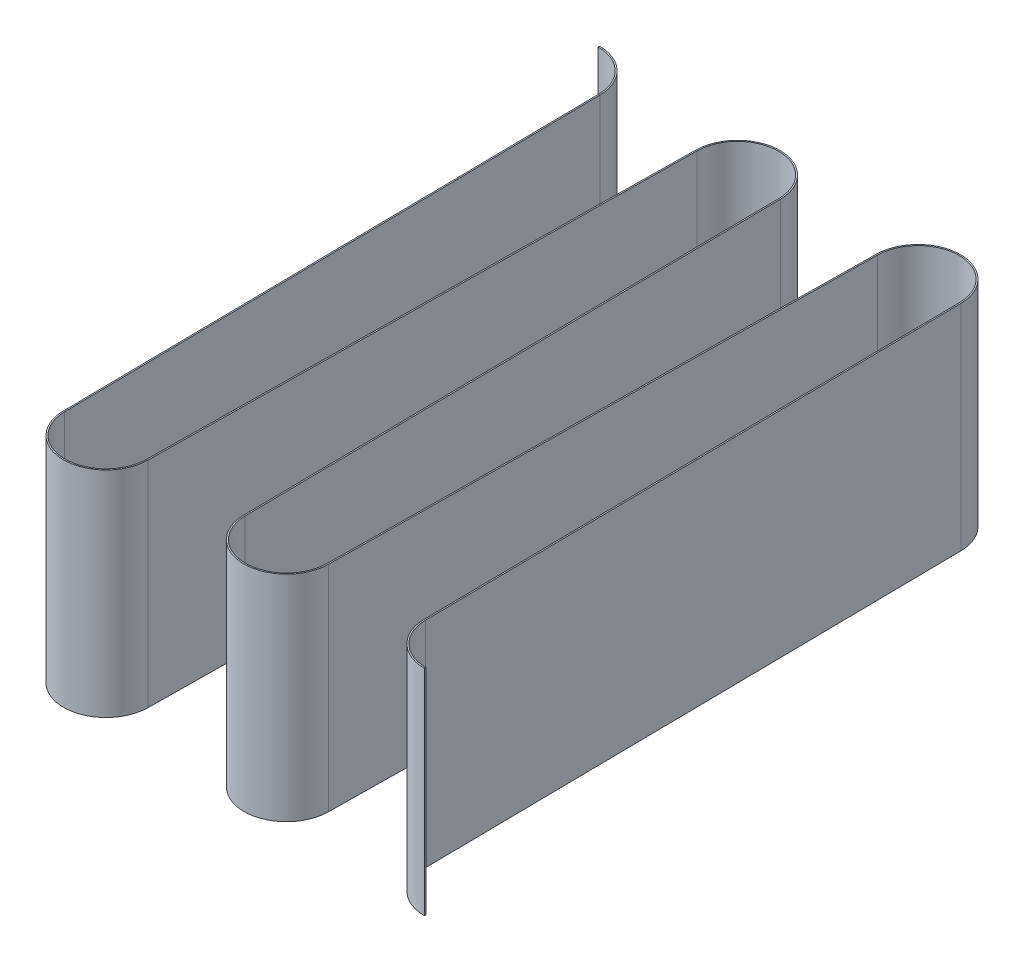
SolidWorks part; units mm, degrees
material "Corrugated Paper"
ref_plane "Front" through (0, 0, 0) normal (0, 0, 1) x (1, 0, 0)
ref_plane "Top" through (0, 0, 0) normal (0, 1, 0) x (1, 0, 0)
ref_plane "Right" through (0, 0, 0) normal (1, 0, 0) x (0, 0, -1)
sketch "Sketch1" plane through (0, 0, 0) normal (0, 1, 0) x (1, 0, 0)
  line L0 (-50.5, 40.4) -> (-50.5, 60.6) construction
  line L1 (-41.1507, 60.7156) -> (-39.6493, -60.7156) construction
  line L2 (-19.4493, 60.7156) -> (-20.9507, -60.7156) construction
  line L3 (-0.7507, 60.7156) -> (0.7507, -60.7156) construction
  line L4 (19.4493, -60.7156) -> (20.9507, 60.7156) construction
  line L5 (39.6493, 60.7156) -> (41.1507, -60.7156) construction
  line L6 (-41.3007, 60.7137) -> (-39.7993, -60.7175)
  line L7 (-19.2993, 60.7137) -> (-20.8007, -60.7175)
  line L8 (-0.9007, 60.7137) -> (0.6007, -60.7175)
  line L9 (19.5993, -60.7175) -> (21.1007, 60.7137)
  line L10 (39.4993, 60.7137) -> (41.0007, -60.7175)
  line L11 (-41.0007, 60.7175) -> (-39.4993, -60.7137)
  line L12 (-19.5993, 60.7175) -> (-21.1007, -60.7137)
  line L13 (-0.6007, 60.7175) -> (0.9007, -60.7137)
  line L14 (19.2993, -60.7137) -> (20.8007, 60.7175)
  line L15 (39.7993, 60.7175) -> (41.3007, -60.7137)
  line L16 (-50.5, 69.8) -> (-50.5, 70.1)
  line L17 (50.5, -70.1) -> (50.5, -69.8)
  circle A0 centre (-50.5, 60.6) radius 9.35 construction
  circle A1 centre (-30.3, 60.6) radius 9.35 construction
  circle A2 centre (-10.1, 60.6) radius 9.35 construction
  circle A3 centre (10.1, 60.6) radius 9.35 construction
  circle A4 centre (30.3, 60.6) radius 9.35 construction
  circle A5 centre (50.5, 60.6) radius 9.35 construction
  circle A6 centre (-30.3, 40.4) radius 9.35 construction
  circle A7 centre (-10.1, 40.4) radius 9.35 construction
  circle A8 centre (10.1, 40.4) radius 9.35 construction
  circle A9 centre (30.3, 40.4) radius 9.35 construction
  circle A10 centre (50.5, 40.4) radius 9.35 construction
  circle A11 centre (-30.3, 20.2) radius 9.35 construction
  circle A12 centre (-10.1, 20.2) radius 9.35 construction
  circle A13 centre (10.1, 20.2) radius 9.35 construction
  circle A14 centre (30.3, 20.2) radius 9.35 construction
  circle A15 centre (50.5, 20.2) radius 9.35 construction
  circle A16 centre (-30.3, 0) radius 9.35 construction
  circle A17 centre (-10.1, 0) radius 9.35 construction
  circle A18 centre (10.1, 0) radius 9.35 construction
  circle A19 centre (30.3, 0) radius 9.35 construction
  circle A20 centre (50.5, 0) radius 9.35 construction
  circle A21 centre (-30.3, -20.2) radius 9.35 construction
  circle A22 centre (-10.1, -20.2) radius 9.35 construction
  circle A23 centre (10.1, -20.2) radius 9.35 construction
  circle A24 centre (30.3, -20.2) radius 9.35 construction
  circle A25 centre (50.5, -20.2) radius 9.35 construction
  circle A26 centre (-30.3, -40.4) radius 9.35 construction
  circle A27 centre (-10.1, -40.4) radius 9.35 construction
  circle A28 centre (10.1, -40.4) radius 9.35 construction
  circle A29 centre (30.3, -40.4) radius 9.35 construction
  circle A30 centre (50.5, -40.4) radius 9.35 construction
  circle A31 centre (-30.3, -60.6) radius 9.35 construction
  circle A32 centre (-10.1, -60.6) radius 9.35 construction
  circle A33 centre (10.1, -60.6) radius 9.35 construction
  circle A34 centre (30.3, -60.6) radius 9.35 construction
  circle A35 centre (50.5, -60.6) radius 9.35 construction
  circle A36 centre (-50.5, 40.4) radius 9.35 construction
  circle A37 centre (-50.5, 20.2) radius 9.35 construction
  circle A38 centre (-50.5, 0) radius 9.35 construction
  circle A39 centre (-50.5, -20.2) radius 9.35 construction
  circle A40 centre (-50.5, -40.4) radius 9.35 construction
  circle A41 centre (-50.5, -60.6) radius 9.35 construction
  arc A42 (-50.5, 69.95) -> (-41.1507, 60.7156) centre (-50.5, 60.6) cw construction
  arc A43 (-39.6493, -60.7156) -> (-20.9507, -60.7156) centre (-30.3, -60.6) ccw construction
  arc A44 (-19.4493, 60.7156) -> (-0.7507, 60.7156) centre (-10.1, 60.6) cw construction
  arc A45 (0.7507, -60.7156) -> (19.4493, -60.7156) centre (10.1, -60.6) ccw construction
  arc A46 (20.9507, 60.7156) -> (39.6493, 60.7156) centre (30.3, 60.6) cw construction
  arc A47 (41.1507, -60.7156) -> (50.5, -69.95) centre (50.5, -60.6) ccw construction
  arc A48 (-50.5, 69.8) -> (-41.3007, 60.7137) centre (-50.5, 60.6) cw
  arc A49 (-39.7993, -60.7175) -> (-20.8007, -60.7175) centre (-30.3, -60.6) ccw
  arc A50 (-19.2993, 60.7137) -> (-0.9007, 60.7137) centre (-10.1, 60.6) cw
  arc A51 (0.6007, -60.7175) -> (19.5993, -60.7175) centre (10.1, -60.6) ccw
  arc A52 (21.1007, 60.7137) -> (39.4993, 60.7137) centre (30.3, 60.6) cw
  arc A53 (41.0007, -60.7175) -> (50.5, -70.1) centre (50.5, -60.6) ccw
  arc A54 (-50.5, 70.1) -> (-41.0007, 60.7175) centre (-50.5, 60.6) cw
  arc A55 (-39.4993, -60.7137) -> (-21.1007, -60.7137) centre (-30.3, -60.6) ccw
  arc A56 (-19.5993, 60.7175) -> (-0.6007, 60.7175) centre (-10.1, 60.6) cw
  arc A57 (0.9007, -60.7137) -> (19.2993, -60.7137) centre (10.1, -60.6) ccw
  arc A58 (20.8007, 60.7175) -> (39.7993, 60.7175) centre (30.3, 60.6) cw
  arc A59 (41.3007, -60.7137) -> (50.5, -69.8) centre (50.5, -60.6) ccw
  point P103 (0, 0)
  dimension "D1" = 18.7
  dimension "D6" = 20.2
  dimension "D7" = 20.2
  dimension "D2" = 60.6
  dimension "D3" = 50.5
  dimension "D8" = 0.15
  dimension "D9" = 0.15
  dimension "D4" = 6
  dimension "D5" = 7
extrude "Boss-Extrude1" add sketch "Sketch1" along normal mid plane 48
